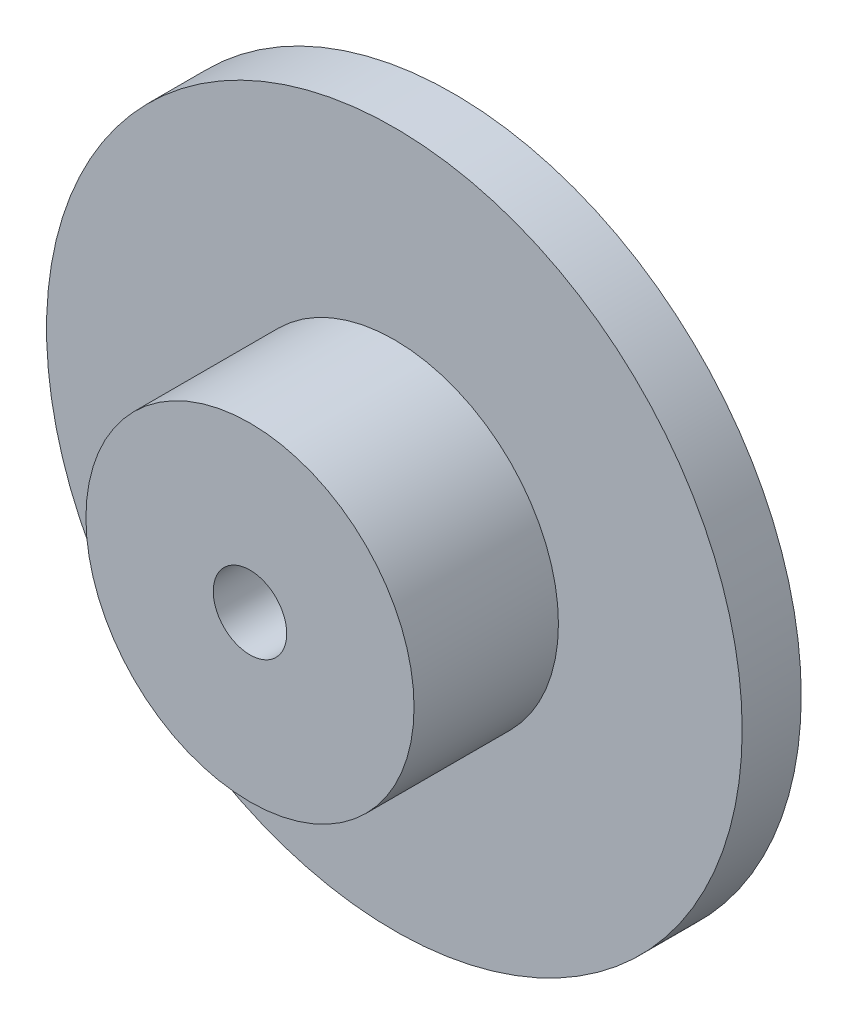
SolidWorks part; units mm, degrees
ref_plane "Plan de face" through (0, 0, 0) normal (0, 0, 1) x (1, 0, 0)
ref_plane "Plan de dessus" through (0, 0, 0) normal (0, 1, 0) x (1, 0, 0)
ref_plane "Plan de droite" through (0, 0, 0) normal (1, 0, 0) x (0, 0, -1)
sketch "Esquisse1" plane through (0, 0, 0) normal (0, 0, 1) x (1, 0, 0)
  circle A0 centre (0, 0) radius 26.5
  circle A1 centre (0, 0) radius 3
  dimension "D1" = 53
  dimension "D2" = 6
extrude "Boss.-Extru.1" add sketch "Esquisse1" against normal blind 4.5
sketch "Esquisse2" plane through (0, 0, 0) normal (0, 0, 1) x (1, 0, 0)
  circle A0 centre (0, 0) radius 12.5
  circle A2 centre (0, 0) radius 2.8
  dimension "D1" = 25
  dimension "D2" = 5.6
extrude "Boss.-Extru.2" add sketch "Esquisse2" along normal blind 11
